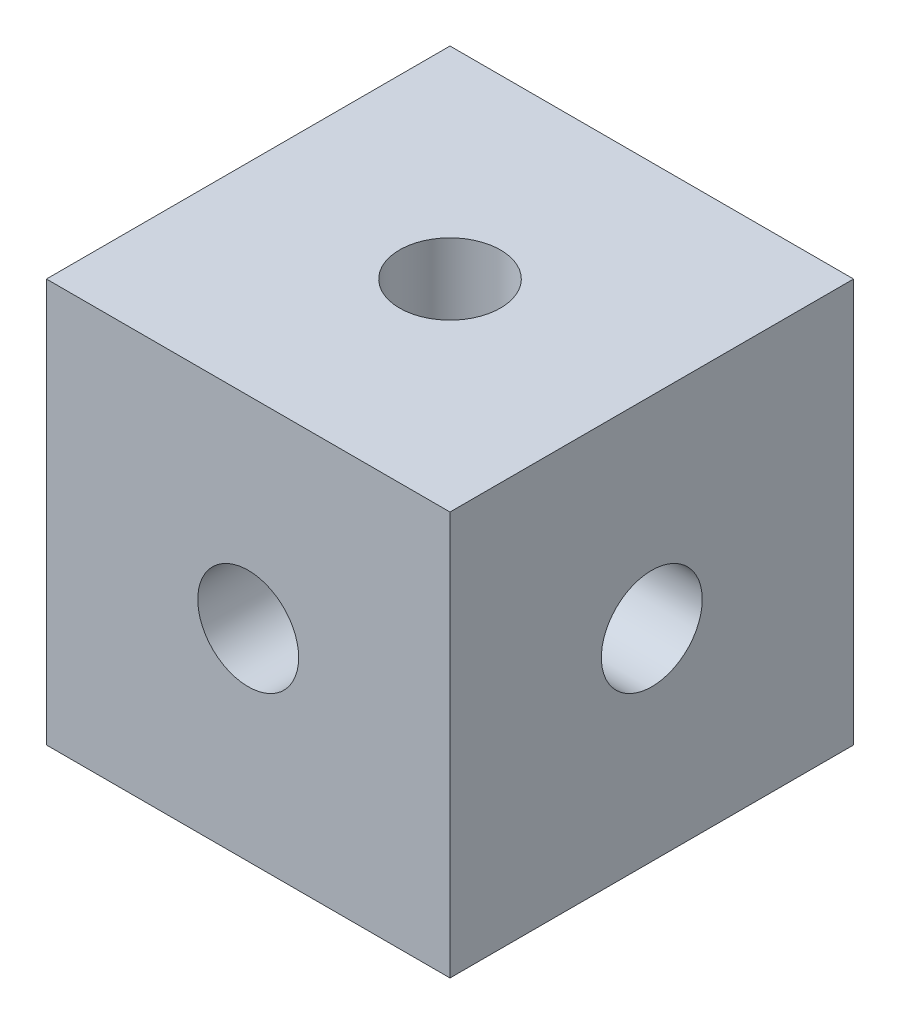
SolidWorks part; units mm, degrees
material "6061-T6 (SS)"
ref_plane "前视基准面" through (0, 0, 0) normal (0, 0, 1) x (1, 0, 0)
ref_plane "上视基准面" through (0, 0, 0) normal (0, 1, 0) x (1, 0, 0)
ref_plane "右视基准面" through (0, 0, 0) normal (1, 0, 0) x (0, 0, -1)
sketch "草图1" plane through (0, 0, 0) normal (0, 1, 0) x (1, 0, 0)
  line L1 (-5, -5) -> (5, -5)
  line L2 (-5, -5) -> (-5, 5)
  line L3 (-5, 5) -> (5, 5)
  line L4 (5, -5) -> (5, 5)
  line L5 (-5, -5) -> (5, 5) construction
  line L6 (-5, 5) -> (5, -5) construction
  point P0 (0, 0)
  dimension "D1" = 10
extrude "凸台-拉伸1" add sketch "草图1" along normal mid plane 10
hole_wizard "M3 螺纹孔1" positions "草图3" profile "草图4" tap size "M3" standard "GB" end condition through all
sketch "草图3" plane through (0, 0, 5) normal (0, 0, 1) x (1, 0, 0)
  point P0 (0, 0)
sketch "草图4" plane through (0, 0, 5) normal (1, 0, 0) x (0, -1, 0)
  line L0 (0, 0) -> (0, 10)
  line L1 (0, 10) -> (1.25, 10)
  line L2 (1.25, 10) -> (1.25, 0)
  line L5 (1.25, 0) -> (0, 0)
  line L11 (0, -6.35) -> (0, 107.95) construction
  dimension "通孔螺纹孔钻头直径" = 2.5
  dimension "通孔螺纹孔钻头深度" = 10
cosmetic thread "孔螺蚊线1"
hole_wizard "M3 螺纹孔2" positions "草图5" profile "草图6" tap size "M3" standard "GB" end condition through all
sketch "草图5" plane through (5, 0, 0) normal (1, 0, 0) x (0, 0, -1)
  point P0 (0, 0)
cosmetic thread "孔螺蚊线2"
sketch "草图6" plane through (5, 0, 0) normal (0, 1, 0) x (0, 0, -1)
  line L0 (0, 0) -> (0, 10)
  line L1 (0, 10) -> (1.25, 10)
  line L2 (1.25, 10) -> (1.25, 0)
  line L5 (1.25, 0) -> (0, 0)
  line L11 (0, -6.35) -> (0, 107.95) construction
  dimension "通孔螺纹孔钻头直径" = 2.5
  dimension "通孔螺纹孔钻头深度" = 10
hole_wizard "M3 螺纹孔3" positions "草图7" profile "草图8" tap size "M3" standard "GB" end condition through all
sketch "草图7" plane through (0, 5, 0) normal (0, 1, 0) x (1, 0, 0)
  point P0 (0, 0)
sketch "草图8" plane through (0, 5, 0) normal (1, 0, 0) x (0, 0, 1)
  line L0 (0, 0) -> (0, 10)
  line L1 (0, 10) -> (1.25, 10)
  line L2 (1.25, 10) -> (1.25, 0)
  line L5 (1.25, 0) -> (0, 0)
  line L11 (0, -6.35) -> (0, 107.95) construction
  dimension "通孔螺纹孔钻头直径" = 2.5
  dimension "通孔螺纹孔钻头深度" = 10
cosmetic thread "孔螺蚊线3"
